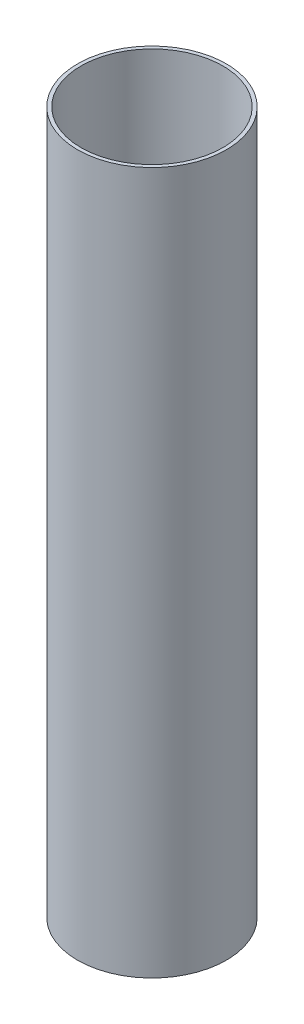
SolidWorks part; units mm, degrees
ref_plane "Front Plane" through (0, 0, 0) normal (0, 0, 1) x (1, 0, 0)
ref_plane "Top Plane" through (0, 0, 0) normal (0, 1, 0) x (1, 0, 0)
ref_plane "Right Plane" through (0, 0, 0) normal (1, 0, 0) x (0, 0, -1)
sketch "Sketch1" plane through (0, 0, 0) normal (0, 1, 0) x (1, 0, 0)
  circle A0 centre (0, 0) radius 21
  dimension "D1" = 42
extrude "Boss-Extrude1" add sketch "Sketch1" along normal blind 198
sketch "Sketch2" plane through (0, 198, 0) normal (0, 1, 0) x (1, 0, 0)
  circle A0 centre (0, 0) radius 20
  dimension "D1" = 40
extrude "Cut-Extrude1" cut sketch "Sketch2" against normal blind 198
